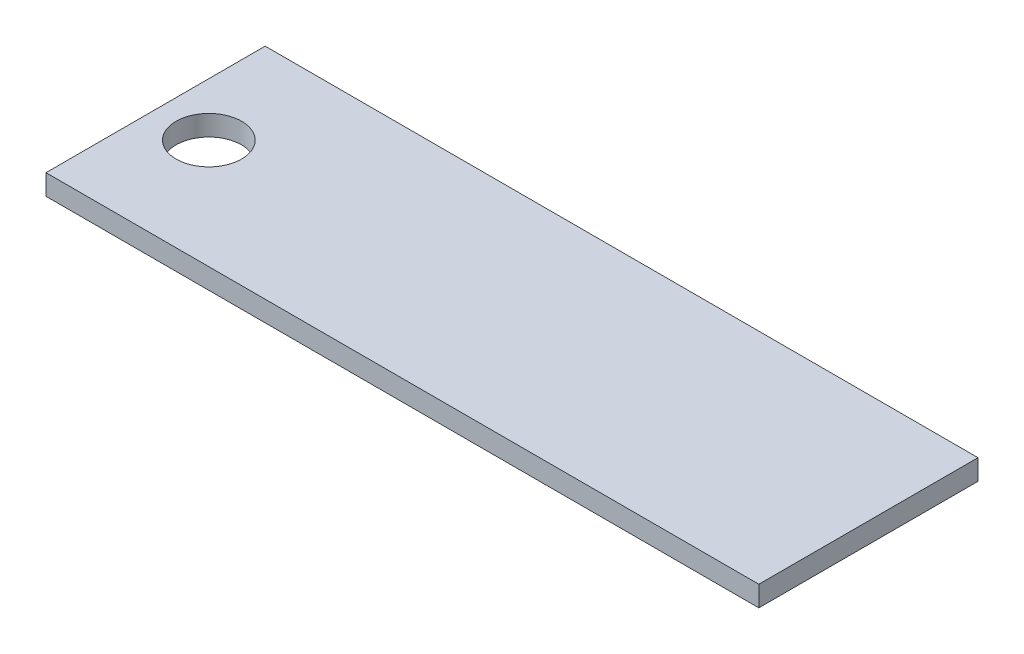
SolidWorks part; units mm, degrees
ref_plane "Front Plane" through (0, 0, 0) normal (0, 0, 1) x (1, 0, 0)
ref_plane "Top Plane" through (0, 0, 0) normal (0, 1, 0) x (1, 0, 0)
ref_plane "Right Plane" through (0, 0, 0) normal (1, 0, 0) x (0, 0, -1)
sketch "Sketch1" plane through (0, 0, 0) normal (0, 1, 0) x (1, 0, 0)
  line L1 (0, 0) -> (34.8, 0)
  line L2 (0, 0) -> (0, 10.7)
  line L3 (0, 10.7) -> (34.8, 10.7)
  line L4 (34.8, 0) -> (34.8, 10.7)
  circle A0 centre (2.6, 5.35) radius 1.6
  dimension "D3" = 3.2
  dimension "D1" = 34.8
  dimension "D2" = 10.7
  dimension "D4" = 5.35
  dimension "D5" = 2.6
extrude "Boss-Extrude1" add sketch "Sketch1" along normal blind 1
